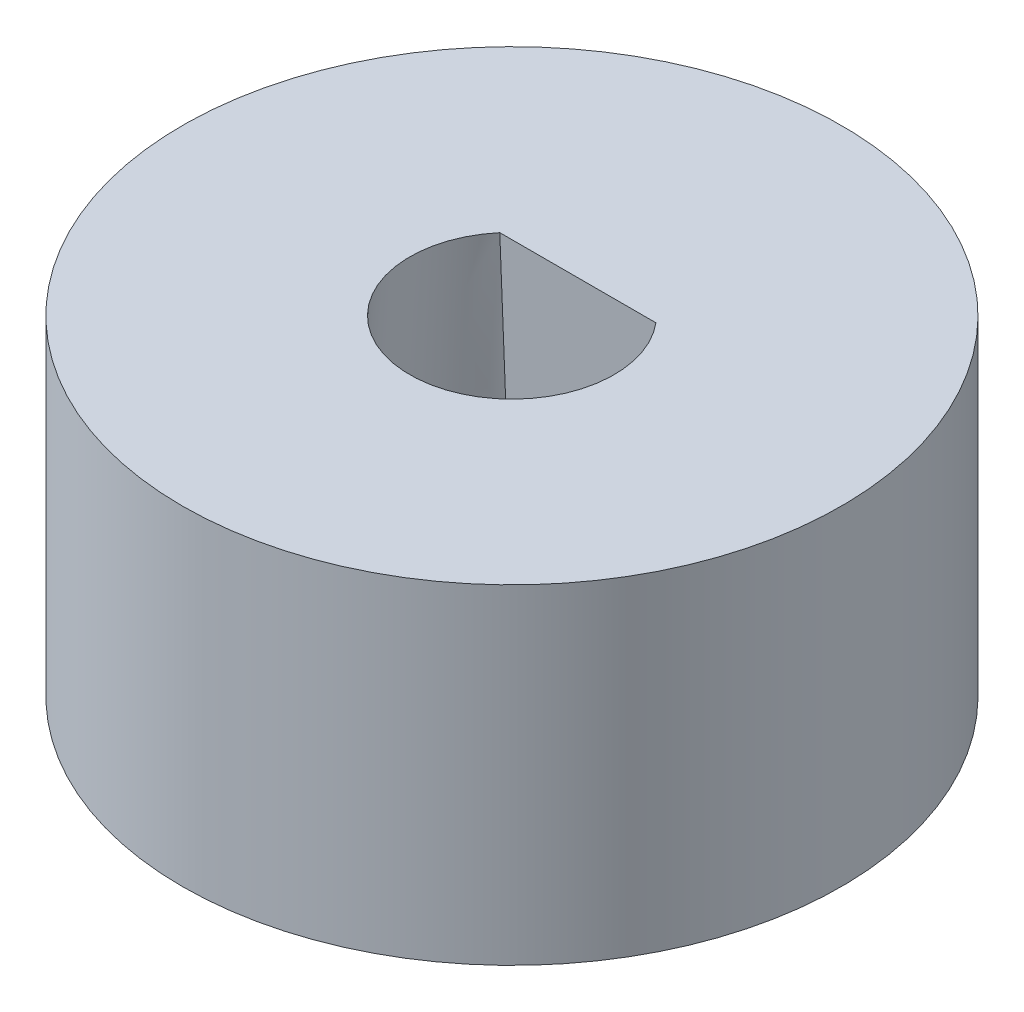
SolidWorks part; units mm, degrees
ref_plane "Front Plane" through (0, 0, 0) normal (0, 0, 1) x (1, 0, 0)
ref_plane "Top Plane" through (0, 0, 0) normal (0, 1, 0) x (1, 0, 0)
ref_plane "Right Plane" through (0, 0, 0) normal (1, 0, 0) x (0, 0, -1)
sketch "Sketch1" plane through (0, 0, 0) normal (0, 1, 0) x (1, 0, 0)
  line L0 (0, -1.55) -> (0, 1) construction
  line L1 (0, 1) -> (1.1843, 1)
  line L2 (1.1843, 1) -> (-1.1843, 1)
  circle A0 centre (0, 0) radius 1.55
  circle A1 centre (0, 0) radius 5
  point P8 (0, 1)
  dimension "D1" = 3.1
  dimension "D3" = 10
  dimension "D2" = 2.55
extrude "Boss-Extrude1" add sketch "Sketch1" along normal blind 5 contours L1 A0 L2 | A1 A0
draft "Draft12" type of draft neutral plane draft angle 4 faces to draft 2 face at (0, 2.5, 0.275) face at (0, 2.5, -1) neutral plane through (0, 5, 0) neutral plane normal (0, 1, 0) reverse direction yes parameters "D1"=4
